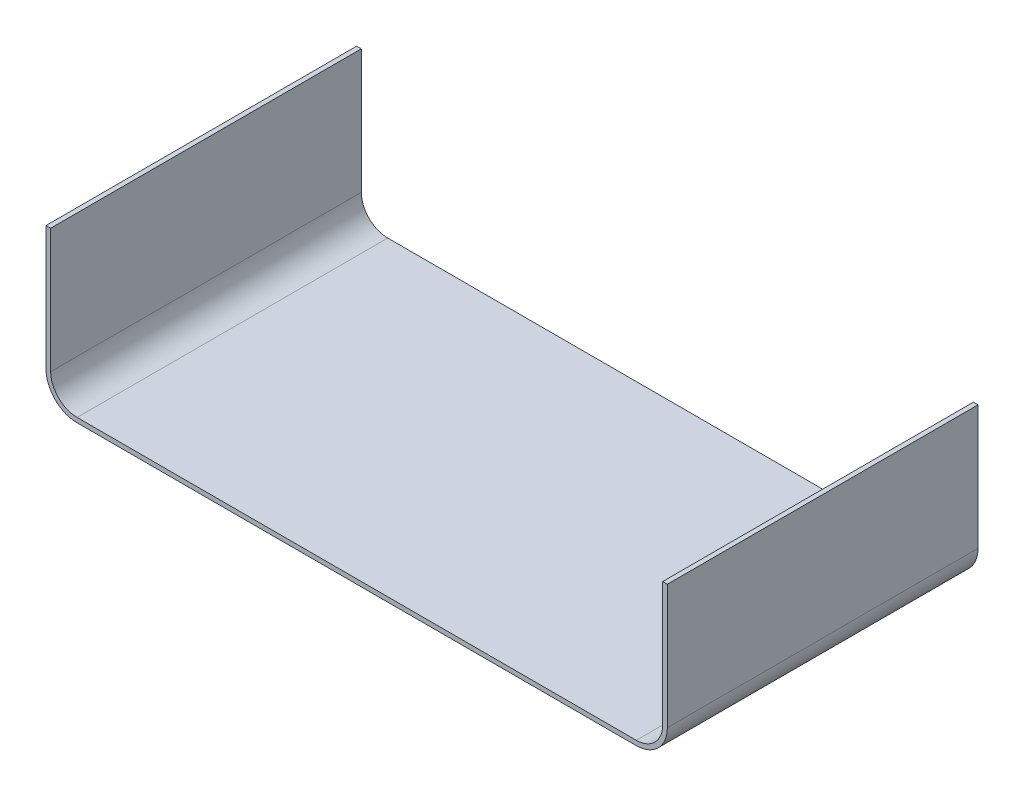
SolidWorks part; units mm, degrees
ref_plane "前基準面" through (0, 0, 0) normal (0, 0, 1) x (1, 0, 0)
ref_plane "上基準面" through (0, 0, 0) normal (0, 1, 0) x (1, 0, 0)
ref_plane "右基準面" through (0, 0, 0) normal (1, 0, 0) x (0, 0, -1)
sketch "草圖1" plane through (0, 0, 0) normal (0, 0, 1) x (1, 0, 0)
  line L0 (-200, 100) -> (-200, 0)
  line L1 (-200, 0) -> (200, 0)
  line L2 (200, 0) -> (200, 100)
  line L3 (-200, 100) -> (200, 100) construction
  line L4 (-200, 100) -> (200, 100)
  dimension "D1" = 400
  dimension "D3" = 100
extrude "伸長1" add sketch "草圖1" along normal blind 200
fillet "圓角1" radius 20 2 edges at (200, 0, 100) (-200, 0, 100)
shell "薄殼1" thickness 3
